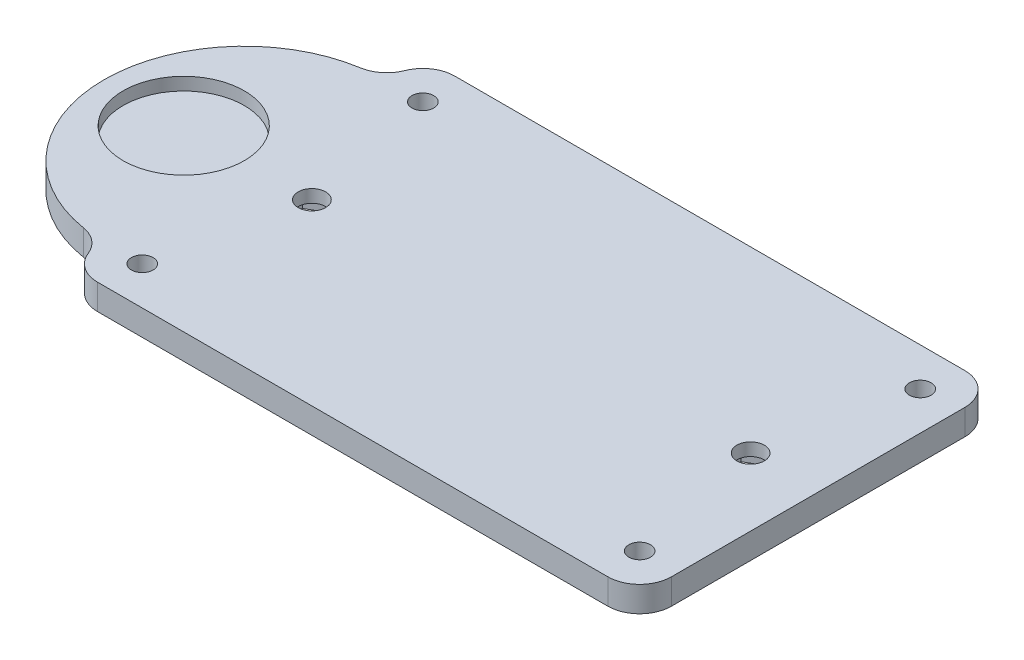
SolidWorks part; units mm, degrees
ref_plane "Front Plane" through (0, 0, 0) normal (0, 0, 1) x (1, 0, 0)
ref_plane "Top Plane" through (0, 0, 0) normal (0, 1, 0) x (1, 0, 0)
ref_plane "Right Plane" through (0, 0, 0) normal (1, 0, 0) x (0, 0, -1)
sketch "Sketch1" plane through (0, 0, 0) normal (0, 1, 0) x (1, 0, 0)
  line L1 (-45, 28) -> (45, 28)
  line L2 (-45, 28) -> (-45, -28)
  line L3 (-45, -28) -> (45, -28)
  line L4 (45, 28) -> (45, -28)
  dimension "D1" = 90
  dimension "D2" = 56
  dimension "D3" = 45
  dimension "D4" = 28
extrude "Boss-Extrude1" add sketch "Sketch1" along normal blind 4
sketch "Sketch2" plane through (0, 4, 0) normal (0, 1, 0) x (1, 0, 0)
  line L0 (-45, -28) -> (45, -28) construction
  line L1 (45, -28) -> (45, 28) construction
  line L2 (-45, 28) -> (-45, -28) construction
  circle A0 centre (-34.4, 0) radius 2.15
  circle A1 centre (34.4, 0) radius 2.15
  circle A2 centre (-39.0023, -22) radius 1.7
  circle A3 centre (39, -22) radius 1.7
  circle A4 centre (39, 22) radius 1.7
  circle A5 centre (-39, 22) radius 1.7
  dimension "D1" = 4.3
  dimension "D3" = 28
  dimension "D4" = 10.6
  dimension "D5" = 68.8
  dimension "D6" = 3.4
  dimension "D7" = 6
  dimension "D8" = 5.9977
  dimension "D9" = 6
  dimension "D10" = 6
  dimension "D11" = 6
  dimension "D12" = 6
  dimension "D13" = 22
  dimension "D14" = 22
  dimension "D2" = 28
extrude "Cut-Extrude1" cut sketch "Sketch2" against normal blind 4
sketch "Sketch3" plane through (0, 0, 0) normal (0, -1, 0) x (1, 0, 0)
  line L0 (45, 28) -> (45, -28) construction
  line L1 (30.825, -2.064) -> (34.4, -4.1281)
  line L2 (34.4, -4.1281) -> (37.975, -2.064)
  line L3 (37.975, -2.064) -> (37.975, 2.064)
  line L4 (37.975, 2.064) -> (34.4, 4.1281)
  line L5 (34.4, 4.1281) -> (30.825, 2.064)
  line L6 (30.825, 2.064) -> (30.825, -2.064)
  line L7 (-37.975, -2.064) -> (-34.4, -4.1281)
  line L8 (-34.4, -4.1281) -> (-30.825, -2.064)
  line L9 (-30.825, -2.064) -> (-30.825, 2.064)
  line L10 (-30.825, 2.064) -> (-34.4, 4.1281)
  line L11 (-34.4, 4.1281) -> (-37.975, 2.064)
  line L12 (-37.975, 2.064) -> (-37.975, -2.064)
  line L14 (-45, -28) -> (-45, 28) construction
  circle A0 centre (34.4, 0) radius 3.575 construction
  circle A1 centre (-34.4, 0) radius 3.575 construction
  point P22 (30.825, 0)
  dimension "D1" = 7.15
  dimension "D2" = 7.15
extrude "Cut-Extrude2" cut sketch "Sketch3" against normal blind 2
sketch "Sketch4" plane through (0, 4, 0) normal (0, 1, 0) x (1, 0, 0)
  line L0 (-45, 28) -> (-45, -28) construction
  line L1 (-45, -22) -> (-45, 22)
  arc A0 (-45, 22) -> (-45, -22) centre (-45, 0) ccw
  dimension "D1" = 22
extrude "Boss-Extrude3" add sketch "Sketch4" against normal blind 4
sketch "Sketch6" plane through (0, 4, 0) normal (0, 1, 0) x (1, 0, 0)
  line L0 (-45, -22) -> (-45, -28) construction
  circle A0 centre (-54.5, 0) radius 9.5
  point P2 (0, 0)
  point P4 (0, 0)
  point P7 (0, 0)
  dimension "D1" = 19
extrude "Cut-Extrude3" cut sketch "Sketch6" against normal blind 2
fillet "Fillet1" radius 5 4 edges at (45, 2, 28) (45, 2, -28) (-45, 2, -28) (-45, 2, 28)
fillet "Fillet2" radius 5 2 edges at (-45, 2, -22) (-45, 2, 22)
